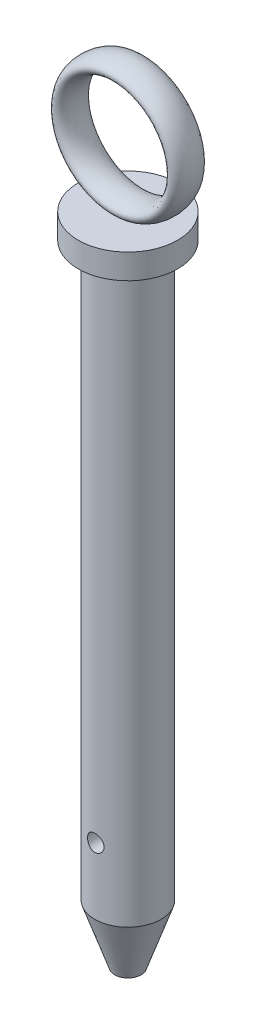
SolidWorks part; units mm, degrees
ref_plane "前视基准面" through (0, 0, 0) normal (0, 0, 1) x (1, 0, 0)
ref_plane "上视基准面" through (0, 0, 0) normal (0, 1, 0) x (1, 0, 0)
ref_plane "右视基准面" through (0, 0, 0) normal (1, 0, 0) x (0, 0, -1)
sketch "草图1" plane through (0, 0, 0) normal (0, 0, 1) x (1, 0, 0)
  line L0 (0, 0) -> (0, 395)
  line L1 (0, 395) -> (-30, 395)
  line L2 (-30, 395) -> (-30, 380)
  line L3 (-30, 380) -> (-20, 380)
  line L4 (-20, 380) -> (-20, 35)
  line L5 (-20, 35) -> (-8, 0)
  line L6 (-8, 0) -> (0, 0)
  line L7 (0, -1000) -> (0, 49000) construction
  dimension "D1" = 395
  dimension "D2" = 30
  dimension "D3" = 15
  dimension "D4" = 10
  dimension "D5" = 345
  dimension "D6" = 8
revolve "旋转1" add sketch "草图1" angle 360 about L7
ref_plane "基准面1" through (0, 0, 30) normal (0, 0, 1) x (1, 0, 0)
sketch "草图2" plane through (0, 0, 30) normal (0, 0, 1) x (1, 0, 0)
  line L0 (0, -1000) -> (0, 49000) construction
  line L1 (-20, 380) -> (20, 380) construction
  circle A0 centre (0, 75) radius 5
  dimension "D1" = 10
  dimension "D2" = 305
extrude "切除-拉伸1" cut sketch "草图2" against normal through all
ref_plane "基准面2" through (0, 435, 0) normal (0, 1, 0) x (1, 0, 0)
sketch "草图3" plane through (0, 435, 0) normal (0, 1, 0) x (1, 0, 0)
  line L0 (0, -1000) -> (0, 49000) construction
  line L1 (-1000, 0) -> (49000, 0) construction
  ellipse E0 centre (35, 0) end of major axis (35, -10) minor radius 5
  dimension "D2" = 20
  dimension "D1" = 10
  dimension "D3" = 35
revolve "旋转2" add sketch "草图3" angle 360 about L0
